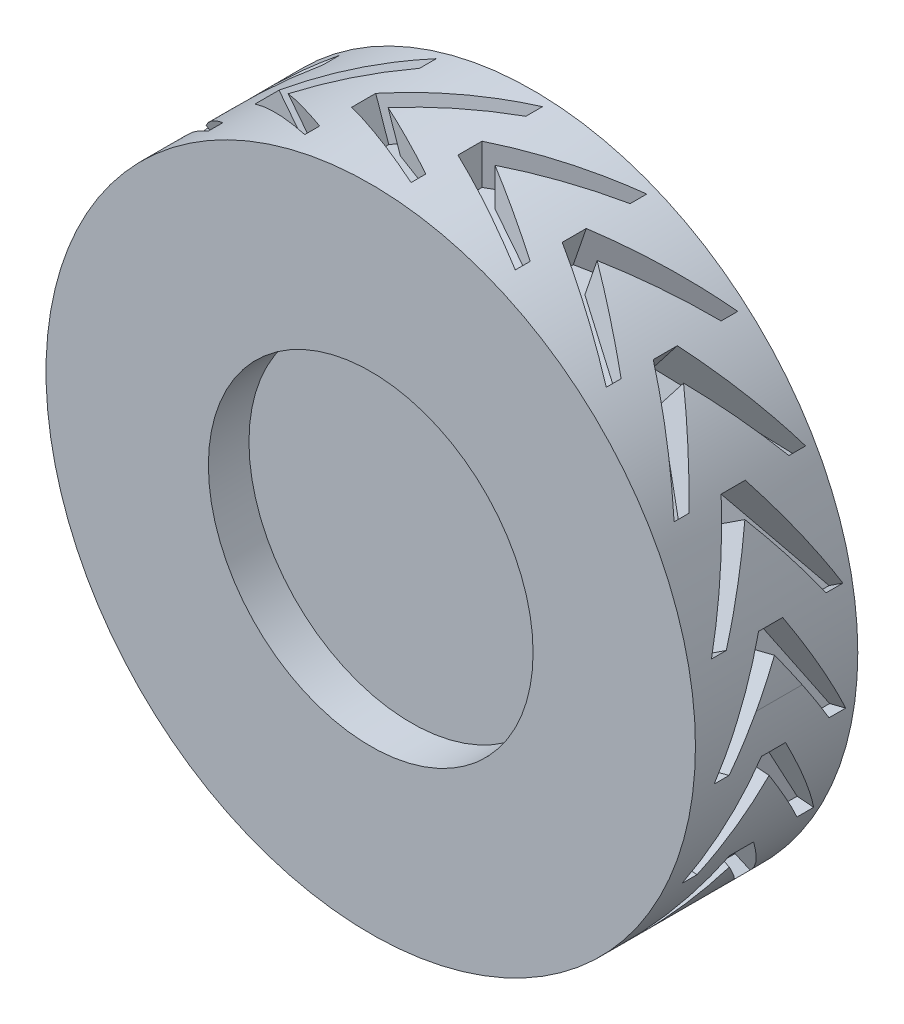
SolidWorks part; units mm, degrees
ref_plane "Front Plane" through (0, 0, 0) normal (0, 0, 1) x (1, 0, 0)
ref_plane "Top Plane" through (0, 0, 0) normal (0, 1, 0) x (1, 0, 0)
ref_plane "Right Plane" through (0, 0, 0) normal (1, 0, 0) x (0, 0, -1)
sketch "Sketch1" plane through (0, 0, 0) normal (0, 0, 1) x (1, 0, 0)
  circle A0 centre (0, 0) radius 40
  dimension "D1" = 80
extrude "Boss-Extrude1" add sketch "Sketch1" along normal mid plane 20
sketch "Sketch2" plane through (0, 0, 10) normal (0, 0, 1) x (1, 0, 0)
  circle A0 centre (0, 0) radius 20
  dimension "D1" = 40
extrude "Cut-Extrude1" cut sketch "Sketch2" against normal blind 5
ref_plane "Plane1" through (0, 40, 0) normal (0, 1, 0) x (1, 0, 0)
sketch "Sketch3" plane through (0, 40, 0) normal (0, 1, 0) x (1, 0, 0)
  line L0 (15.111, 8.8955) -> (15.111, 6.8427)
  line L1 (15.111, 6.8427) -> (5.3031, 0)
  line L2 (5.3031, 0) -> (15.111, -5.4742)
  line L3 (15.111, -5.4742) -> (15.111, -7.2989)
  line L4 (15.111, -7.2989) -> (2.2239, -1.4826)
  line L5 (2.2239, -1.4826) -> (2.2239, 1.4826)
  line L6 (2.2239, 1.4826) -> (15.111, 8.8955)
extrude "Cut-Extrude2" cut sketch "Sketch3" against normal blind 5
pattern_circular "CirPattern1" count 19 over 360 about axis through (0, 0, 0) along (0, 0, 1) of "Cut-Extrude2"
